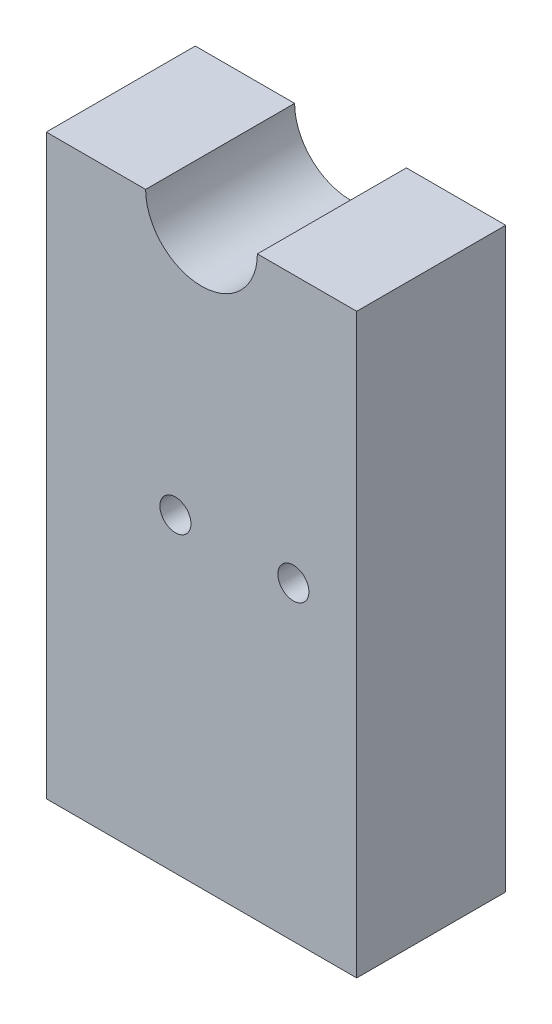
SolidWorks part; units mm, degrees
ref_plane "Front Plane" through (0, 0, 0) normal (0, 0, 1) x (1, 0, 0)
ref_plane "Top Plane" through (0, 0, 0) normal (0, 1, 0) x (1, 0, 0)
ref_plane "Right Plane" through (0, 0, 0) normal (1, 0, 0) x (0, 0, -1)
sketch "Sketch1" plane through (0, 0, 0) normal (0, 0, 1) x (1, 0, 0)
  line L0 (-12.5, 0) -> (12.5, 0)
  line L1 (12.5, 0) -> (12.5, 46.5)
  line L2 (12.5, 46.5) -> (4.5, 46.5)
  line L3 (-12.5, 46.5) -> (-12.5, 0)
  line L4 (-4.5, 46.5) -> (-12.5, 46.5)
  line L5 (-19.0331, 46.5) -> (19.9284, 46.5) construction
  arc A0 (-4.5, 46.5) -> (4.5, 46.5) centre (0, 46.5) ccw
  dimension "D1" = 4.5
  dimension "D2" = 25
  dimension "D3" = 46.5
extrude "Boss-Extrude1" add sketch "Sketch1" along normal blind 12
sketch "Sketch2" plane through (0, 0, 0) normal (0, 0, -1) x (-1, 0, 0)
  line L0 (-7.4, 25) -> (2.1, 25) construction
  line L1 (12.5, 0) -> (-12.5, 0) construction
  line L2 (-12.5, 0) -> (-12.5, 46.5) construction
  circle A0 centre (-7.4, 25) radius 1.25
  circle A1 centre (2.1, 25) radius 1.25
  dimension "D3" = 2.5
  dimension "D1" = 25
  dimension "D2" = 5.1
  dimension "D4" = 9.5
extrude "Cut-Extrude1" cut sketch "Sketch2" against normal through all both and the other way through all
